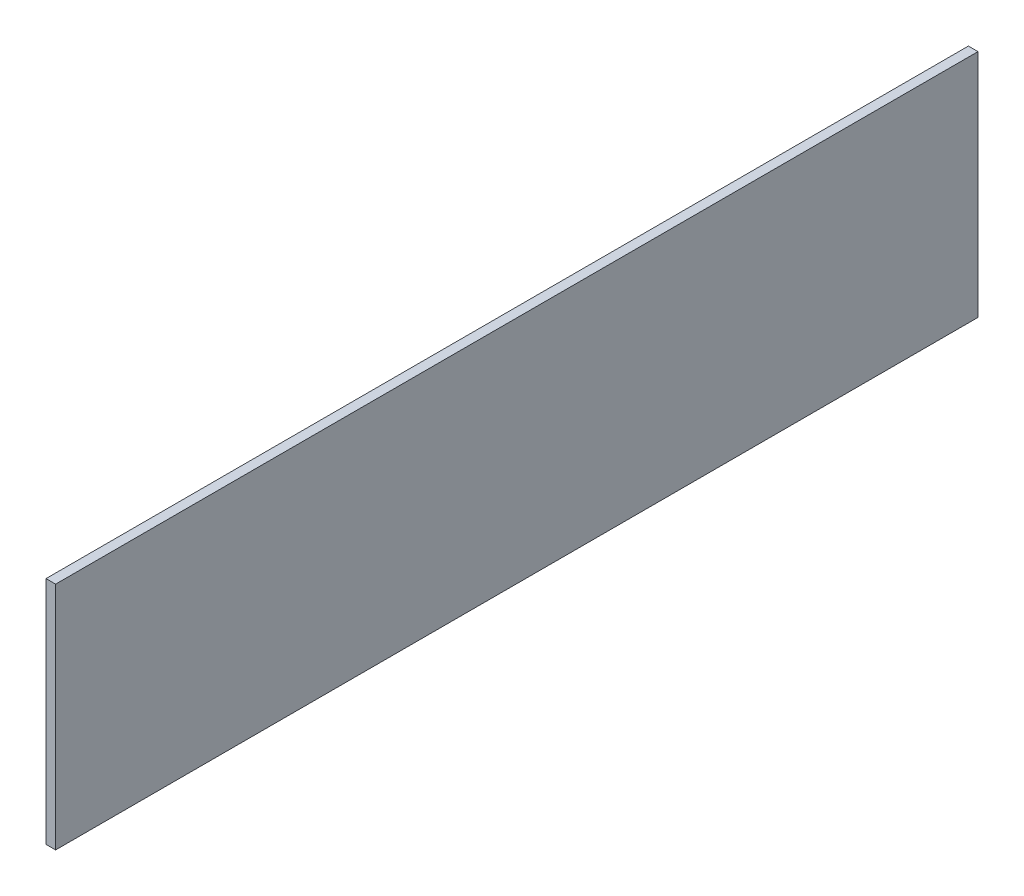
SolidWorks part; units mm, degrees
ref_plane "Front Plane" through (0, 0, 0) normal (0, 0, 1) x (1, 0, 0)
ref_plane "Top Plane" through (0, 0, 0) normal (0, 1, 0) x (1, 0, 0)
ref_plane "Right Plane" through (0, 0, 0) normal (1, 0, 0) x (0, 0, -1)
sketch "Sketch1" plane through (0, 0, 0) normal (1, 0, 0) x (0, 0, -1)
  line L1 (0, 0) -> (304.8, 0)
  line L2 (0, 0) -> (0, -76.073)
  line L3 (0, -76.073) -> (304.8, -76.073)
  line L4 (304.8, 0) -> (304.8, -76.073)
  dimension "D1" = 76.073
  dimension "D2" = 304.8
extrude "Boss-Extrude1" add sketch "Sketch1" along normal blind 3.175
sketch "Sketch2" plane through (0, 0, 0) normal (0, 0, 1) x (1, 0, 0)
  line L0 (1.5875, 0) -> (1.5875, -76.073) construction
  line L1 (3.175, 0) -> (0, 0) construction
  line L2 (3.175, -76.073) -> (0, -76.073) construction
sketch "Sketch3" plane through (0, 0, -304.8) normal (0, 0, -1) x (-1, 0, 0)
  line L0 (-1.5875, 0) -> (-1.5875, -76.073) construction
  line L1 (-3.175, 0) -> (0, 0) construction
  line L2 (-3.175, -76.073) -> (0, -76.073) construction
